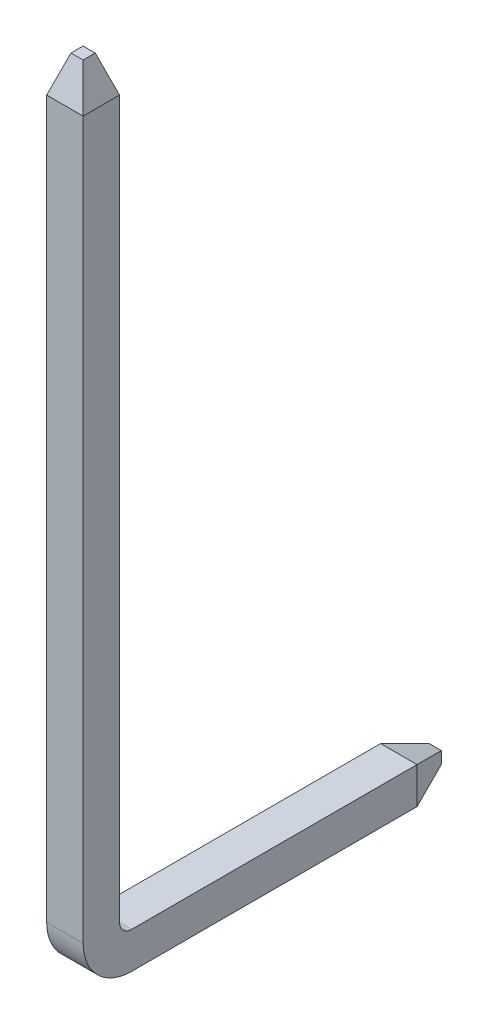
SolidWorks part; units mm, degrees
material "Nickel"
ref_plane "Ebene vorne" through (0, 0, 0) normal (0, 0, 1) x (1, 0, 0)
ref_plane "Ebene oben" through (0, 0, 0) normal (0, 1, 0) x (1, 0, 0)
ref_plane "Ebene rechts" through (0, 0, 0) normal (1, 0, 0) x (0, 0, -1)
sketch "Skizze1" plane through (0, 0, 0) normal (1, 0, 0) x (0, 0, -1)
  line L0 (0, 0.2) -> (0, 12.6)
  line L1 (0, 12.6) -> (-0.6, 12.6)
  line L2 (-0.6, 12.6) -> (-0.6, 0.2)
  line L3 (0.2, -0.6) -> (5.5, -0.6)
  line L4 (5.5, -0.6) -> (5.5, 0)
  line L5 (5.5, 0) -> (0.2, 0)
  arc A0 (0, 0.2) -> (0.2, 0) centre (0.2, 0.2) ccw
  arc A1 (-0.6, 0.2) -> (0.2, -0.6) centre (0.2, 0.2) ccw
  point P9 (0, 0)
  point P12 (-0.6, -0.6)
  dimension "D4" = 0.2
  dimension "D5" = 0.8
  dimension "D1" = 0.6
  dimension "D2" = 6.1
  dimension "D3" = 13.2
extrude "Aufsatz-Linear austragen1" add sketch "Skizze1" along normal blind 0.6
chamfer "Fase1" distance 0.2 distance2 0.6 8 edges at (0, -0.3, -5.5) (0.3, -0.6, -5.5) (0.3, 0, -5.5) (0.6, -0.3, -5.5) (0.3, 12.6, 0.6) (0, 12.6, 0.3) (0.3, 12.6, 0) (0.6, 12.6, 0.3)
